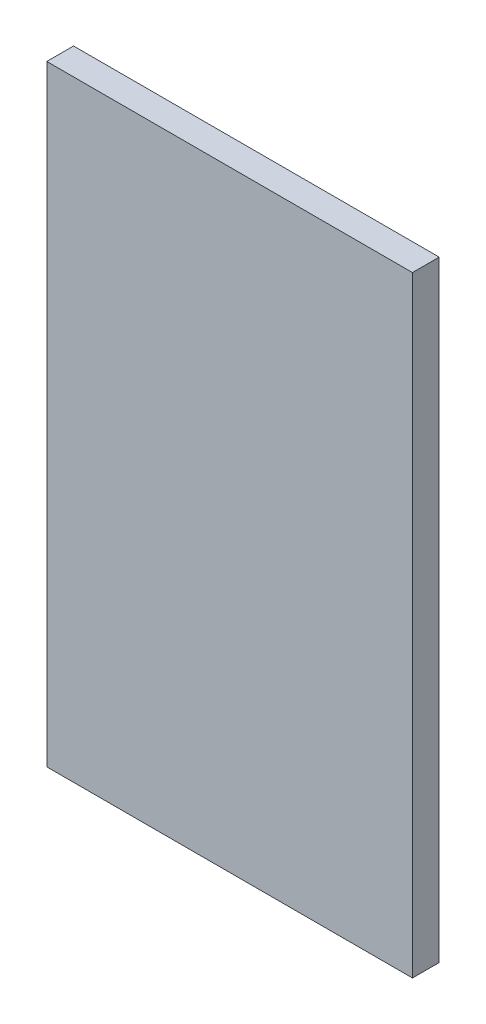
SolidWorks part; units mm, degrees
material "Pine"
ref_plane "Front Plane" through (0, 0, 0) normal (0, 0, 1) x (1, 0, 0)
ref_plane "Top Plane" through (0, 0, 0) normal (0, 1, 0) x (1, 0, 0)
ref_plane "Right Plane" through (0, 0, 0) normal (1, 0, 0) x (0, 0, -1)
sketch "Sketch3" plane through (0, 0, 0) normal (0, 0, 1) x (1, 0, 0)
  line L4 (419, 204) -> (583, 204)
  line L5 (419, 204) -> (419, -70)
  line L6 (419, -70) -> (583, -70)
  line L7 (583, 204) -> (583, -70)
  line L8 (419, 204) -> (583, -70) construction
  line L9 (419, -70) -> (583, 204) construction
  point P6 (501, 67)
  dimension "D1" = 164
  dimension "D2" = 274
extrude "Boss-Extrude2" add sketch "Sketch3" along normal blind 12 separate body
sketch "Sketch4" [suppressed] plane through (0, 0, 12) normal (0, 0, 1) x (1, 0, 0)
  line L1 (442.6085, 191.5854) -> (556.8131, 191.5854)
  line L2 (432.6085, 181.5854) -> (432.6085, 99.4004)
  line L3 (442.6085, 89.4004) -> (556.8131, 89.4004)
  line L4 (566.8131, 181.5854) -> (566.8131, 99.4004)
  line L5 (432.6085, 191.5854) -> (566.8131, 89.4004) construction
  line L6 (432.6085, 89.4004) -> (566.8131, 191.5854) construction
  line L7 (438.5839, 77.616) -> (560.5839, 77.616) construction
  line L8 (438.5839, 77.616) -> (438.5839, -46.384) construction
  line L9 (438.5839, -46.384) -> (560.5839, -46.384) construction
  line L10 (560.5839, 77.616) -> (560.5839, -46.384) construction
  line L11 (213.067, 66.7937) -> (345.067, 66.7937) construction
  line L12 (213.067, 66.7937) -> (213.067, -0.2063) construction
  line L13 (213.067, -0.2063) -> (345.067, -0.2063) construction
  line L14 (345.067, 66.7937) -> (345.067, -0.2063) construction
  line L15 (465.4441, 183.8582) -> (567.4441, 183.8582)
  line L16 (465.4441, 183.8582) -> (465.4441, 98.8582)
  line L17 (465.4441, 98.8582) -> (567.4441, 98.8582)
  line L18 (567.4441, 183.8582) -> (567.4441, 98.8582)
  arc A0 (432.6085, 99.4004) -> (442.6085, 89.4004) centre (442.6085, 99.4004) ccw
  arc A1 (556.8131, 89.4004) -> (566.8131, 99.4004) centre (556.8131, 99.4004) ccw
  arc A2 (556.8131, 191.5854) -> (566.8131, 181.5854) centre (556.8131, 181.5854) cw
  arc A3 (442.6085, 191.5854) -> (432.6085, 181.5854) centre (442.6085, 181.5854) ccw
  point P0 (499.7108, 140.4929)
  dimension "D1" = 10
equation "\"LENGTH\" = 1000mm"
equation "\"PLY\"= 12mm"
equation "\"CENTER_BRACE_LENGTH\" = 393mm"
equation "\"PANEL_WIDTH\"= \"LENGTH\" - \"CENTER_BRACE_LENGTH\" * 2 - \"PLY\" * 4"
equation "\"D1@Boss-Extrude2\"=\"PLY\""
equation "\"D1@Sketch3\"=\"PANEL_WIDTH\" - 2"
equation "\"PANEL_SMALL_HEIGHT\" = 70mm"
equation "\"D2@Sketch3\"=\"WIDTH\" - \"PLY\" * 2 - 2"
equation "\"WIDTH\" = 300mm"
